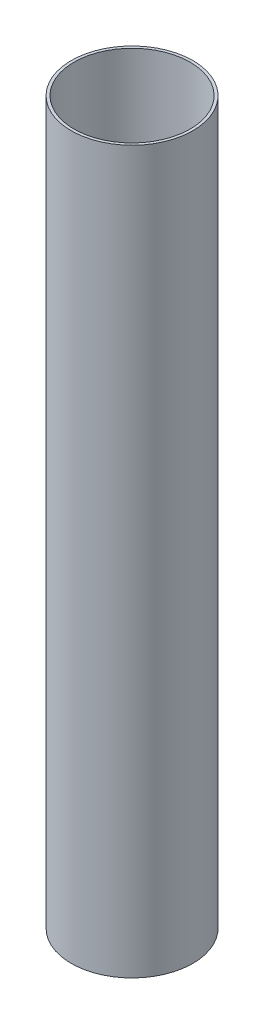
SolidWorks part; units mm, degrees
material "ASTM A36 Steel"
ref_plane "Front Plane" through (0, 0, 0) normal (0, 0, 1) x (1, 0, 0)
ref_plane "Top Plane" through (0, 0, 0) normal (0, 1, 0) x (1, 0, 0)
ref_plane "Right Plane" through (0, 0, 0) normal (1, 0, 0) x (0, 0, -1)
sketch "Sketch1" plane through (0, 0, 0) normal (0, 1, 0) x (1, 0, 0)
  circle A0 centre (0, 0) radius 109.55
  dimension "D1" = 219.1
extrude "Extrude-Thin1" add sketch "Sketch1" along normal blind 1299 thin thin type one direction reverse wall 5
